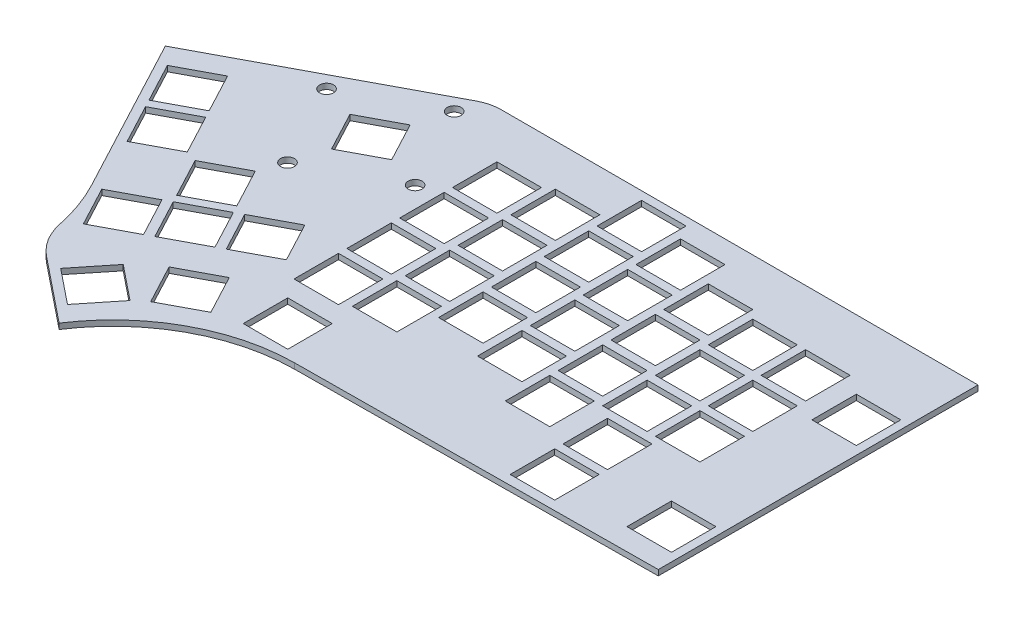
SolidWorks part; units mm, degrees
ref_plane "Front Plane" through (0, 0, 0) normal (0, 0, 1) x (1, 0, 0)
ref_plane "Top Plane" through (0, 0, 0) normal (0, 1, 0) x (1, 0, 0)
ref_plane "Right Plane" through (0, 0, 0) normal (1, 0, 0) x (0, 0, -1)
sketch "Main" plane through (0, 0, 0) normal (0, 1, 0) x (1, 0, 0)
  line L0 (6.4754, 3.5) -> (12.8, 6.5) construction
  line L1 (0, 0) -> (18, 0) construction
  line L2 (0, 0) -> (0, 18) construction
  line L3 (0, 18) -> (18, 18) construction
  line L4 (18, 0) -> (18, 18) construction
  line L5 (2, 16) -> (16, 16)
  line L6 (2, 16) -> (2, 2)
  line L7 (2, 2) -> (16, 2)
  line L8 (16, 16) -> (16, 2)
  line L18 (9, 9) -> (6.4754, 3.5) construction
  line L20 (9, 9) -> (12.8, 6.5) construction
  line L22 (25.4754, 5.5) -> (31.8, 8.5) construction
  line L23 (19, 2) -> (37, 2) construction
  line L24 (19, 2) -> (19, 20) construction
  line L25 (19, 20) -> (37, 20) construction
  line L26 (37, 2) -> (37, 20) construction
  line L27 (21, 18) -> (35, 18)
  line L28 (21, 18) -> (21, 4)
  line L29 (21, 4) -> (35, 4)
  line L30 (35, 18) -> (35, 4)
  line L31 (28, 11) -> (25.4754, 5.5) construction
  line L32 (28, 11) -> (31.8, 8.5) construction
  line L33 (44.4754, 17.5) -> (50.8, 20.5) construction
  line L34 (38, 14) -> (56, 14) construction
  line L35 (38, 14) -> (38, 32) construction
  line L36 (38, 32) -> (56, 32) construction
  line L37 (56, 14) -> (56, 32) construction
  line L38 (40, 30) -> (54, 30)
  line L39 (40, 30) -> (40, 16)
  line L40 (40, 16) -> (54, 16)
  line L41 (54, 30) -> (54, 16)
  line L42 (47, 23) -> (44.4754, 17.5) construction
  line L43 (47, 23) -> (50.8, 20.5) construction
  line L44 (63.4754, 12.5) -> (69.8, 15.5) construction
  line L45 (57, 9) -> (75, 9) construction
  line L46 (57, 9) -> (57, 27) construction
  line L47 (57, 27) -> (75, 27) construction
  line L48 (75, 9) -> (75, 27) construction
  line L49 (59, 25) -> (73, 25)
  line L50 (59, 25) -> (59, 11)
  line L51 (59, 11) -> (73, 11)
  line L52 (73, 25) -> (73, 11)
  line L53 (66, 18) -> (63.4754, 12.5) construction
  line L54 (66, 18) -> (69.8, 15.5) construction
  line L55 (82.4754, 3.5) -> (88.8, 6.5) construction
  line L56 (76, 0) -> (94, 0) construction
  line L57 (76, 0) -> (76, 18) construction
  line L58 (76, 18) -> (94, 18) construction
  line L59 (94, 0) -> (94, 18) construction
  line L60 (78, 16) -> (92, 16)
  line L61 (78, 16) -> (78, 2)
  line L62 (78, 2) -> (92, 2)
  line L63 (92, 16) -> (92, 2)
  line L64 (85, 9) -> (82.4754, 3.5) construction
  line L65 (85, 9) -> (88.8, 6.5) construction
  line L66 (101.4754, 0.5) -> (107.8, 3.5) construction
  line L67 (95, -3) -> (113, -3) construction
  line L68 (95, -3) -> (95, 15) construction
  line L69 (95, 15) -> (113, 15) construction
  line L70 (113, -3) -> (113, 15) construction
  line L71 (97, 13) -> (111, 13)
  line L72 (97, 13) -> (97, -1)
  line L73 (97, -1) -> (111, -1)
  line L74 (111, 13) -> (111, -1)
  line L75 (104, 6) -> (101.4754, 0.5) construction
  line L76 (104, 6) -> (107.8, 3.5) construction
  line L77 (120.4754, 0.5) -> (126.8, 3.5) construction
  line L78 (114, -3) -> (132, -3) construction
  line L79 (114, -3) -> (114, 15) construction
  line L80 (114, 15) -> (132, 15) construction
  line L81 (132, -3) -> (132, 15) construction
  line L82 (116, 13) -> (130, 13)
  line L83 (116, 13) -> (116, -1)
  line L84 (116, -1) -> (130, -1)
  line L85 (130, 13) -> (130, -1)
  line L86 (123, 6) -> (120.4754, 0.5) construction
  line L87 (123, 6) -> (126.8, 3.5) construction
  line L88 (2, -3) -> (16, -3)
  line L89 (2, -3) -> (2, -17)
  line L90 (2, -17) -> (16, -17)
  line L91 (16, -3) -> (16, -17)
  line L92 (21, -1) -> (35, -1)
  line L93 (21, -1) -> (21, -15)
  line L94 (21, -15) -> (35, -15)
  line L95 (35, -1) -> (35, -15)
  line L96 (40, 11) -> (54, 11)
  line L97 (40, 11) -> (40, -3)
  line L98 (40, -3) -> (54, -3)
  line L99 (54, 11) -> (54, -3)
  line L100 (59, 6) -> (73, 6)
  line L101 (59, 6) -> (59, -8)
  line L102 (59, -8) -> (73, -8)
  line L103 (73, 6) -> (73, -8)
  line L104 (78, -3) -> (92, -3)
  line L105 (78, -3) -> (78, -17)
  line L106 (78, -17) -> (92, -17)
  line L107 (92, -3) -> (92, -17)
  line L108 (97, -6) -> (111, -6)
  line L109 (97, -6) -> (97, -20)
  line L110 (97, -20) -> (111, -20)
  line L111 (111, -6) -> (111, -20)
  line L112 (116, -6) -> (130, -6)
  line L113 (116, -6) -> (116, -20)
  line L114 (116, -20) -> (130, -20)
  line L115 (130, -6) -> (130, -20)
  line L116 (6.4754, -15.5) -> (12.8, -12.5) construction
  line L117 (0, -19) -> (18, -19) construction
  line L118 (0, -19) -> (0, -1) construction
  line L119 (0, -1) -> (18, -1) construction
  line L120 (18, -19) -> (18, -1) construction
  line L121 (9, -10) -> (6.4754, -15.5) construction
  line L122 (9, -10) -> (12.8, -12.5) construction
  line L123 (25.4754, -13.5) -> (31.8, -10.5) construction
  line L124 (19, -17) -> (37, -17) construction
  line L125 (19, -17) -> (19, 1) construction
  line L126 (19, 1) -> (37, 1) construction
  line L127 (37, -17) -> (37, 1) construction
  line L128 (28, -8) -> (25.4754, -13.5) construction
  line L129 (28, -8) -> (31.8, -10.5) construction
  line L130 (44.4754, -1.5) -> (50.8, 1.5) construction
  line L131 (38, -5) -> (56, -5) construction
  line L132 (38, -5) -> (38, 13) construction
  line L133 (38, 13) -> (56, 13) construction
  line L134 (56, -5) -> (56, 13) construction
  line L135 (47, 4) -> (44.4754, -1.5) construction
  line L136 (47, 4) -> (50.8, 1.5) construction
  line L137 (63.4754, -6.5) -> (69.8, -3.5) construction
  line L138 (57, -10) -> (75, -10) construction
  line L139 (57, -10) -> (57, 8) construction
  line L140 (57, 8) -> (75, 8) construction
  line L141 (75, -10) -> (75, 8) construction
  line L142 (66, -1) -> (63.4754, -6.5) construction
  line L143 (66, -1) -> (69.8, -3.5) construction
  line L144 (82.4754, -15.5) -> (88.8, -12.5) construction
  line L145 (76, -19) -> (94, -19) construction
  line L146 (76, -19) -> (76, -1) construction
  line L147 (76, -1) -> (94, -1) construction
  line L148 (94, -19) -> (94, -1) construction
  line L149 (85, -10) -> (82.4754, -15.5) construction
  line L150 (85, -10) -> (88.8, -12.5) construction
  line L151 (101.4754, -18.5) -> (107.8, -15.5) construction
  line L152 (95, -22) -> (113, -22) construction
  line L153 (95, -22) -> (95, -4) construction
  line L154 (95, -4) -> (113, -4) construction
  line L155 (113, -22) -> (113, -4) construction
  line L156 (104, -13) -> (101.4754, -18.5) construction
  line L157 (104, -13) -> (107.8, -15.5) construction
  line L158 (120.4754, -18.5) -> (126.8, -15.5) construction
  line L159 (114, -22) -> (132, -22) construction
  line L160 (114, -22) -> (114, -4) construction
  line L161 (114, -4) -> (132, -4) construction
  line L162 (132, -22) -> (132, -4) construction
  line L163 (123, -13) -> (120.4754, -18.5) construction
  line L164 (123, -13) -> (126.8, -15.5) construction
  line L165 (2, -22) -> (16, -22)
  line L166 (2, -22) -> (2, -36)
  line L167 (2, -36) -> (16, -36)
  line L168 (16, -22) -> (16, -36)
  line L169 (21, -20) -> (35, -20)
  line L170 (21, -20) -> (21, -34)
  line L171 (21, -34) -> (35, -34)
  line L172 (35, -20) -> (35, -34)
  line L173 (40, -8) -> (54, -8)
  line L174 (40, -8) -> (40, -22)
  line L175 (40, -22) -> (54, -22)
  line L176 (54, -8) -> (54, -22)
  line L177 (59, -13) -> (73, -13)
  line L178 (59, -13) -> (59, -27)
  line L179 (59, -27) -> (73, -27)
  line L180 (73, -13) -> (73, -27)
  line L181 (78, -22) -> (92, -22)
  line L182 (78, -22) -> (78, -36)
  line L183 (78, -36) -> (92, -36)
  line L184 (92, -22) -> (92, -36)
  line L185 (97, -25) -> (111, -25)
  line L186 (97, -25) -> (97, -39)
  line L187 (97, -39) -> (111, -39)
  line L188 (111, -25) -> (111, -39)
  line L189 (116, -25) -> (130, -25)
  line L190 (116, -25) -> (116, -39)
  line L191 (116, -39) -> (130, -39)
  line L192 (130, -25) -> (130, -39)
  line L193 (6.4754, -34.5) -> (12.8, -31.5) construction
  line L194 (0, -38) -> (18, -38) construction
  line L195 (0, -38) -> (0, -20) construction
  line L196 (0, -20) -> (18, -20) construction
  line L197 (18, -38) -> (18, -20) construction
  line L198 (9, -29) -> (6.4754, -34.5) construction
  line L199 (9, -29) -> (12.8, -31.5) construction
  line L200 (25.4754, -32.5) -> (31.8, -29.5) construction
  line L201 (19, -36) -> (37, -36) construction
  line L202 (19, -36) -> (19, -18) construction
  line L203 (19, -18) -> (37, -18) construction
  line L204 (37, -36) -> (37, -18) construction
  line L205 (28, -27) -> (25.4754, -32.5) construction
  line L206 (28, -27) -> (31.8, -29.5) construction
  line L207 (44.4754, -20.5) -> (50.8, -17.5) construction
  line L208 (38, -24) -> (56, -24) construction
  line L209 (38, -24) -> (38, -6) construction
  line L210 (38, -6) -> (56, -6) construction
  line L211 (56, -24) -> (56, -6) construction
  line L212 (47, -15) -> (44.4754, -20.5) construction
  line L213 (47, -15) -> (50.8, -17.5) construction
  line L214 (63.4754, -25.5) -> (69.8, -22.5) construction
  line L215 (57, -29) -> (75, -29) construction
  line L216 (57, -29) -> (57, -11) construction
  line L217 (57, -11) -> (75, -11) construction
  line L218 (75, -29) -> (75, -11) construction
  line L219 (66, -20) -> (63.4754, -25.5) construction
  line L220 (66, -20) -> (69.8, -22.5) construction
  line L221 (82.4754, -34.5) -> (88.8, -31.5) construction
  line L222 (76, -38) -> (94, -38) construction
  line L223 (76, -38) -> (76, -20) construction
  line L224 (76, -20) -> (94, -20) construction
  line L225 (94, -38) -> (94, -20) construction
  line L226 (85, -29) -> (82.4754, -34.5) construction
  line L227 (85, -29) -> (88.8, -31.5) construction
  line L228 (101.4754, -37.5) -> (107.8, -34.5) construction
  line L229 (95, -41) -> (113, -41) construction
  line L230 (95, -41) -> (95, -23) construction
  line L231 (95, -23) -> (113, -23) construction
  line L232 (113, -41) -> (113, -23) construction
  line L233 (104, -32) -> (101.4754, -37.5) construction
  line L234 (104, -32) -> (107.8, -34.5) construction
  line L235 (120.4754, -37.5) -> (126.8, -34.5) construction
  line L236 (114, -41) -> (132, -41) construction
  line L237 (114, -41) -> (114, -23) construction
  line L238 (114, -23) -> (132, -23) construction
  line L239 (132, -41) -> (132, -23) construction
  line L240 (123, -32) -> (120.4754, -37.5) construction
  line L241 (123, -32) -> (126.8, -34.5) construction
  line L242 (2, -41) -> (16, -41)
  line L243 (2, -41) -> (2, -55)
  line L244 (2, -55) -> (16, -55)
  line L245 (16, -41) -> (16, -55)
  line L246 (21, -39) -> (35, -39)
  line L247 (21, -39) -> (21, -53)
  line L248 (21, -53) -> (35, -53)
  line L249 (35, -39) -> (35, -53)
  line L250 (40, -27) -> (54, -27)
  line L251 (40, -27) -> (40, -41)
  line L252 (40, -41) -> (54, -41)
  line L253 (54, -27) -> (54, -41)
  line L254 (59, -32) -> (73, -32)
  line L255 (59, -32) -> (59, -46)
  line L256 (59, -46) -> (73, -46)
  line L257 (73, -32) -> (73, -46)
  line L258 (78, -41) -> (92, -41)
  line L259 (78, -41) -> (78, -55)
  line L260 (78, -55) -> (92, -55)
  line L261 (92, -41) -> (92, -55)
  line L270 (6.4754, -53.5) -> (12.8, -50.5) construction
  line L271 (0, -57) -> (18, -57) construction
  line L272 (0, -57) -> (0, -39) construction
  line L273 (0, -39) -> (18, -39) construction
  line L274 (18, -57) -> (18, -39) construction
  line L275 (9, -48) -> (6.4754, -53.5) construction
  line L276 (9, -48) -> (12.8, -50.5) construction
  line L277 (25.4754, -51.5) -> (31.8, -48.5) construction
  line L278 (19, -55) -> (37, -55) construction
  line L279 (19, -55) -> (19, -37) construction
  line L280 (19, -37) -> (37, -37) construction
  line L281 (37, -55) -> (37, -37) construction
  line L282 (28, -46) -> (25.4754, -51.5) construction
  line L283 (28, -46) -> (31.8, -48.5) construction
  line L284 (44.4754, -39.5) -> (50.8, -36.5) construction
  line L285 (38, -43) -> (56, -43) construction
  line L286 (38, -43) -> (38, -25) construction
  line L287 (38, -25) -> (56, -25) construction
  line L288 (56, -43) -> (56, -25) construction
  line L289 (47, -34) -> (44.4754, -39.5) construction
  line L290 (47, -34) -> (50.8, -36.5) construction
  line L291 (63.4754, -44.5) -> (69.8, -41.5) construction
  line L292 (57, -48) -> (75, -48) construction
  line L293 (57, -48) -> (57, -30) construction
  line L294 (57, -30) -> (75, -30) construction
  line L295 (75, -48) -> (75, -30) construction
  line L296 (66, -39) -> (63.4754, -44.5) construction
  line L297 (66, -39) -> (69.8, -41.5) construction
  line L298 (82.4754, -53.5) -> (88.8, -50.5) construction
  line L299 (76, -57) -> (94, -57) construction
  line L300 (76, -57) -> (76, -39) construction
  line L301 (76, -39) -> (94, -39) construction
  line L302 (94, -57) -> (94, -39) construction
  line L303 (85, -48) -> (82.4754, -53.5) construction
  line L304 (85, -48) -> (88.8, -50.5) construction
  line L319 (97, -44) -> (111, -44)
  line L320 (97, -44) -> (97, -58)
  line L321 (97, -58) -> (111, -58)
  line L322 (111, -44) -> (111, -58)
  line L323 (116, -44) -> (130, -44)
  line L324 (116, -44) -> (116, -58)
  line L325 (116, -58) -> (130, -58)
  line L326 (130, -44) -> (130, -58)
  line L327 (101.4754, -56.5) -> (107.8, -53.5) construction
  line L328 (95, -60) -> (113, -60) construction
  line L329 (95, -60) -> (95, -42) construction
  line L330 (95, -42) -> (113, -42) construction
  line L331 (113, -60) -> (113, -42) construction
  line L332 (104, -51) -> (101.4754, -56.5) construction
  line L333 (104, -51) -> (107.8, -53.5) construction
  line L334 (120.4754, -56.5) -> (126.8, -53.5) construction
  line L335 (114, -60) -> (132, -60) construction
  line L336 (114, -60) -> (114, -42) construction
  line L337 (114, -42) -> (132, -42) construction
  line L338 (132, -60) -> (132, -42) construction
  line L339 (123, -51) -> (120.4754, -56.5) construction
  line L340 (123, -51) -> (126.8, -53.5) construction
  circle A0 centre (9, 9) radius 2 construction
  circle A1 centre (6.4754, 3.5) radius 1.5 construction
  circle A2 centre (12.8, 6.5) radius 1.5 construction
  circle A6 centre (28, 11) radius 2 construction
  circle A7 centre (25.4754, 5.5) radius 1.5 construction
  circle A8 centre (31.8, 8.5) radius 1.5 construction
  circle A9 centre (47, 23) radius 2 construction
  circle A10 centre (44.4754, 17.5) radius 1.5 construction
  circle A11 centre (50.8, 20.5) radius 1.5 construction
  circle A12 centre (66, 18) radius 2 construction
  circle A13 centre (63.4754, 12.5) radius 1.5 construction
  circle A14 centre (69.8, 15.5) radius 1.5 construction
  circle A15 centre (85, 9) radius 2 construction
  circle A16 centre (82.4754, 3.5) radius 1.5 construction
  circle A17 centre (88.8, 6.5) radius 1.5 construction
  circle A18 centre (104, 6) radius 2 construction
  circle A19 centre (101.4754, 0.5) radius 1.5 construction
  circle A20 centre (107.8, 3.5) radius 1.5 construction
  circle A21 centre (123, 6) radius 2 construction
  circle A22 centre (120.4754, 0.5) radius 1.5 construction
  circle A23 centre (126.8, 3.5) radius 1.5 construction
  circle A24 centre (9, -10) radius 2 construction
  circle A25 centre (6.4754, -15.5) radius 1.5 construction
  circle A26 centre (12.8, -12.5) radius 1.5 construction
  circle A27 centre (28, -8) radius 2 construction
  circle A28 centre (25.4754, -13.5) radius 1.5 construction
  circle A29 centre (31.8, -10.5) radius 1.5 construction
  circle A30 centre (47, 4) radius 2 construction
  circle A31 centre (44.4754, -1.5) radius 1.5 construction
  circle A32 centre (50.8, 1.5) radius 1.5 construction
  circle A33 centre (66, -1) radius 2 construction
  circle A34 centre (63.4754, -6.5) radius 1.5 construction
  circle A35 centre (69.8, -3.5) radius 1.5 construction
  circle A36 centre (85, -10) radius 2 construction
  circle A37 centre (82.4754, -15.5) radius 1.5 construction
  circle A38 centre (88.8, -12.5) radius 1.5 construction
  circle A39 centre (104, -13) radius 2 construction
  circle A40 centre (101.4754, -18.5) radius 1.5 construction
  circle A41 centre (107.8, -15.5) radius 1.5 construction
  circle A42 centre (123, -13) radius 2 construction
  circle A43 centre (120.4754, -18.5) radius 1.5 construction
  circle A44 centre (126.8, -15.5) radius 1.5 construction
  circle A45 centre (9, -29) radius 2 construction
  circle A46 centre (6.4754, -34.5) radius 1.5 construction
  circle A47 centre (12.8, -31.5) radius 1.5 construction
  circle A48 centre (28, -27) radius 2 construction
  circle A49 centre (25.4754, -32.5) radius 1.5 construction
  circle A50 centre (31.8, -29.5) radius 1.5 construction
  circle A51 centre (47, -15) radius 2 construction
  circle A52 centre (44.4754, -20.5) radius 1.5 construction
  circle A53 centre (50.8, -17.5) radius 1.5 construction
  circle A54 centre (66, -20) radius 2 construction
  circle A55 centre (63.4754, -25.5) radius 1.5 construction
  circle A56 centre (69.8, -22.5) radius 1.5 construction
  circle A57 centre (85, -29) radius 2 construction
  circle A58 centre (82.4754, -34.5) radius 1.5 construction
  circle A59 centre (88.8, -31.5) radius 1.5 construction
  circle A60 centre (104, -32) radius 2 construction
  circle A61 centre (101.4754, -37.5) radius 1.5 construction
  circle A62 centre (107.8, -34.5) radius 1.5 construction
  circle A63 centre (123, -32) radius 2 construction
  circle A64 centre (120.4754, -37.5) radius 1.5 construction
  circle A65 centre (126.8, -34.5) radius 1.5 construction
  circle A66 centre (9, -48) radius 2 construction
  circle A67 centre (6.4754, -53.5) radius 1.5 construction
  circle A68 centre (12.8, -50.5) radius 1.5 construction
  circle A69 centre (28, -46) radius 2 construction
  circle A70 centre (25.4754, -51.5) radius 1.5 construction
  circle A71 centre (31.8, -48.5) radius 1.5 construction
  circle A72 centre (47, -34) radius 2 construction
  circle A73 centre (44.4754, -39.5) radius 1.5 construction
  circle A74 centre (50.8, -36.5) radius 1.5 construction
  circle A75 centre (66, -39) radius 2 construction
  circle A76 centre (63.4754, -44.5) radius 1.5 construction
  circle A77 centre (69.8, -41.5) radius 1.5 construction
  circle A78 centre (85, -48) radius 2 construction
  circle A79 centre (82.4754, -53.5) radius 1.5 construction
  circle A80 centre (88.8, -50.5) radius 1.5 construction
  circle A87 centre (104, -51) radius 2 construction
  circle A88 centre (101.4754, -56.5) radius 1.5 construction
  circle A89 centre (107.8, -53.5) radius 1.5 construction
  circle A90 centre (123, -51) radius 2 construction
  circle A91 centre (120.4754, -56.5) radius 1.5 construction
  circle A92 centre (126.8, -53.5) radius 1.5 construction
  point P9 (9, 16)
  point P10 (9, 18)
  point P11 (2, 9)
  point P12 (0, 9)
  point P30 (28, 18)
  point P31 (28, 20)
  point P32 (21, 11)
  point P33 (19, 11)
  point P46 (47, 30)
  point P47 (47, 32)
  point P48 (40, 23)
  point P49 (38, 23)
  point P64 (66, 25)
  point P65 (66, 27)
  point P66 (59, 18)
  point P67 (57, 18)
  point P82 (85, 16)
  point P83 (85, 18)
  point P84 (78, 9)
  point P85 (76, 9)
  point P100 (104, 13)
  point P101 (104, 15)
  point P102 (97, 6)
  point P103 (95, 6)
  point P118 (123, 13)
  point P119 (123, 15)
  point P120 (116, 6)
  point P121 (114, 6)
  dimension "D6" = 4
  dimension "D7" = 3
  dimension "D10" = 1
  dimension "D11" = 5
  dimension "D1" = 18
  dimension "D2" = 14
  dimension "D3" = 3.2
  dimension "D4" = 4.5
  dimension "D5" = 7
  dimension "D8" = 1
  dimension "D9" = 12
  dimension "D12" = 1
  dimension "D13" = 2
  dimension "D14" = 1
  dimension "D15" = 9
  dimension "D16" = 1
  dimension "D17" = 3
  dimension "D18" = 1
  dimension "D20" = 1
  dimension "D19" = 4
sketch "EntBckSp" plane through (0, 0, 0) normal (0, 1, 0) x (1, 0, 0)
  line L0 (0, 0) -> (18, 0) construction
  line L1 (139, 8.25) -> (153, 8.25)
  line L2 (139, 8.25) -> (139, -5.75)
  line L3 (139, -5.75) -> (153, -5.75)
  line L4 (153, 8.25) -> (153, -5.75)
  line L5 (137, 15) -> (155, 15) construction
  line L6 (137, 15) -> (137, -12.5) construction
  line L7 (137, -12.5) -> (155, -12.5) construction
  line L8 (155, 15) -> (155, -12.5) construction
  line L9 (2, 2) -> (16, 2) construction
  line L10 (143.4754, -4.25) -> (146, 1.25) construction
  line L11 (146, 1.25) -> (149.8, -1.25) construction
  line L12 (149.8, -1.25) -> (143.4754, -4.25) construction
  line L13 (6.4754, 3.5) -> (12.8, 6.5) construction
  line L14 (9, 9) -> (6.4754, 3.5) construction
  line L15 (9, 9) -> (12.8, 6.5) construction
  line L16 (114, 15) -> (132, 15) construction
  line L17 (132, -3) -> (132, 15) construction
  line L18 (101.75, -44) -> (115.75, -44)
  line L19 (101.75, -44) -> (101.75, -58)
  line L20 (101.75, -58) -> (115.75, -58)
  line L21 (115.75, -44) -> (115.75, -58)
  line L22 (95, -42) -> (122.5, -42) construction
  line L23 (95, -42) -> (95, -60) construction
  line L24 (95, -60) -> (122.5, -60) construction
  line L25 (122.5, -42) -> (122.5, -60) construction
  line L26 (106.2254, -56.5) -> (108.75, -51) construction
  line L27 (108.75, -51) -> (112.55, -53.5) construction
  line L28 (112.55, -53.5) -> (106.2254, -56.5) construction
  line L29 (95, -41) -> (95, -23) construction
  line L30 (95, -41) -> (113, -41) construction
  line L31 (101.75, -63) -> (115.75, -63)
  line L32 (101.75, -63) -> (101.75, -77)
  line L33 (101.75, -77) -> (115.75, -77)
  line L34 (115.75, -63) -> (115.75, -77)
  line L35 (95, -61) -> (122.5, -61) construction
  line L36 (95, -61) -> (95, -79) construction
  line L37 (95, -79) -> (122.5, -79) construction
  line L38 (122.5, -61) -> (122.5, -79) construction
  line L39 (106.2254, -75.5) -> (108.75, -70) construction
  line L40 (108.75, -70) -> (112.55, -72.5) construction
  line L41 (112.55, -72.5) -> (106.2254, -75.5) construction
  line L42 (139, -58.25) -> (153, -58.25)
  line L43 (139, -58.25) -> (139, -72.25)
  line L44 (139, -72.25) -> (153, -72.25)
  line L45 (153, -58.25) -> (153, -72.25)
  line L46 (137, -51.5) -> (155, -51.5) construction
  line L47 (137, -51.5) -> (137, -79) construction
  line L48 (137, -79) -> (155, -79) construction
  line L49 (155, -51.5) -> (155, -79) construction
  line L50 (143.4754, -70.75) -> (146, -65.25) construction
  line L51 (146, -65.25) -> (149.8, -67.75) construction
  line L52 (149.8, -67.75) -> (143.4754, -70.75) construction
  line L66 (6.75, -64) -> (20.75, -64)
  line L67 (6.75, -64) -> (6.75, -78)
  line L68 (6.75, -78) -> (20.75, -78)
  line L69 (20.75, -64) -> (20.75, -78)
  line L70 (0, -62) -> (27.5, -62) construction
  line L71 (0, -62) -> (0, -80) construction
  line L72 (0, -80) -> (27.5, -80) construction
  line L73 (27.5, -62) -> (27.5, -80) construction
  line L74 (11.2254, -76.5) -> (13.75, -71) construction
  line L75 (13.75, -71) -> (17.55, -73.5) construction
  line L76 (17.55, -73.5) -> (11.2254, -76.5) construction
  line L77 (0, -57) -> (18, -57) construction
  line L78 (0, -57) -> (0, -39) construction
  circle A0 centre (146, 1.25) radius 2 construction
  circle A1 centre (143.4754, -4.25) radius 1.5 construction
  circle A2 centre (149.8, -1.25) radius 1.5 construction
  circle A3 centre (9, 9) radius 2 construction
  circle A4 centre (6.4754, 3.5) radius 1.5 construction
  circle A5 centre (108.75, -51) radius 2 construction
  circle A6 centre (106.2254, -56.5) radius 1.5 construction
  circle A7 centre (112.55, -53.5) radius 1.5 construction
  circle A8 centre (108.75, -70) radius 2 construction
  circle A9 centre (106.2254, -75.5) radius 1.5 construction
  circle A10 centre (112.55, -72.5) radius 1.5 construction
  circle A11 centre (146, -65.25) radius 2 construction
  circle A12 centre (143.4754, -70.75) radius 1.5 construction
  circle A13 centre (149.8, -67.75) radius 1.5 construction
  circle A17 centre (13.75, -71) radius 2 construction
  circle A18 centre (11.2254, -76.5) radius 1.5 construction
  circle A19 centre (17.55, -73.5) radius 1.5 construction
  point P14 (146, 8.25)
  point P15 (146, 15)
  point P16 (139, 1.25)
  point P17 (137, 1.25)
  point P51 (108.75, -44)
  point P52 (108.75, -42)
  point P53 (101.75, -51)
  point P54 (95, -51)
  point P87 (146, -58.25)
  point P88 (146, -51.5)
  point P89 (139, -65.25)
  point P90 (137, -65.25)
  point P105 (13.75, -64)
  point P106 (13.75, -62)
  point P107 (6.75, -71)
  point P108 (0, -71)
  dimension "D1" = 27.5
  dimension "D2" = 5
  dimension "D3" = 1
  dimension "D5" = 1
  dimension "D7" = 5
  dimension "D4" = 2
sketch "MoLngGo" plane through (0, 0, 0) normal (0, 1, 0) x (1, 0, 0)
  line L0 (-23.8647, -75.115) -> (-11.5011, -68.5469)
  line L1 (-23.8647, -75.115) -> (-17.2967, -87.4787)
  line L2 (-11.5011, -68.5469) -> (-4.933, -80.9106)
  line L3 (-17.2967, -87.4787) -> (-4.933, -80.9106)
  line L4 (-28.7977, -70.0922) -> (-12.9016, -61.6476) construction
  line L5 (-28.7977, -70.0922) -> (-15.8962, -94.378) construction
  line L6 (-12.9016, -61.6476) -> (0, -85.9334) construction
  line L7 (-15.8962, -94.378) -> (0, -85.9334) construction
  line L8 (-12.9016, -61.6476) -> (-15.8962, -94.378) construction
  line L9 (-23.8647, -75.115) -> (-4.933, -80.9106) construction
  line L10 (0, -62) -> (0, -80) construction
  line L11 (0, -80) -> (27.5, -80) construction
  line L12 (6.75, -78) -> (20.75, -78) construction
  line L13 (-14.3989, -78.0128) -> (13.75, -131) construction
  line L14 (-14.048, -84.0544) -> (-9.8701, -78.4379) construction
  line L15 (-9.8701, -78.4379) -> (-14.3989, -78.0128) construction
  line L16 (-14.3989, -78.0128) -> (-14.048, -84.0544) construction
  line L17 (17.55, -73.5) -> (11.2254, -76.5) construction
  line L18 (11.2254, -76.5) -> (13.75, -71) construction
  line L19 (13.75, -71) -> (17.55, -73.5) construction
  line L20 (-42.8638, -94.4914) -> (-34.0949, -83.5778)
  line L21 (-42.8638, -94.4914) -> (-31.9502, -103.2603)
  line L22 (-34.0949, -83.5778) -> (-23.1813, -92.3467)
  line L23 (-31.9502, -103.2603) -> (-23.1813, -92.3467)
  line L24 (-49.3784, -91.8226) -> (-38.1041, -77.7908) construction
  line L25 (-49.3784, -91.8226) -> (-27.941, -109.0472) construction
  line L26 (-38.1041, -77.7908) -> (-16.6667, -95.0154) construction
  line L27 (-27.941, -109.0472) -> (-16.6667, -95.0154) construction
  line L28 (-38.1041, -77.7908) -> (-27.941, -109.0472) construction
  line L29 (-42.8638, -94.4914) -> (-23.1813, -92.3467) construction
  line L30 (-33.0225, -93.419) -> (13.75, -131) construction
  line L31 (-30.3163, -98.8319) -> (-28.6936, -92.0226) construction
  line L32 (-28.6936, -92.0226) -> (-33.0225, -93.419) construction
  line L33 (-33.0225, -93.419) -> (-30.3163, -98.8319) construction
  line L34 (-26.6363, -45.1647) -> (-14.2726, -38.5966)
  line L35 (-26.6363, -45.1647) -> (-20.0682, -57.5283)
  line L36 (-14.2726, -38.5966) -> (-7.7045, -50.9603)
  line L37 (-20.0682, -57.5283) -> (-7.7045, -50.9603)
  line L38 (-29.3408, -44.3367) -> (-13.4447, -35.8921) construction
  line L39 (-29.3408, -44.3367) -> (-20.8962, -60.2329) construction
  line L40 (-13.4447, -35.8921) -> (-5, -51.7882) construction
  line L41 (-20.8962, -60.2329) -> (-5, -51.7882) construction
  line L42 (-13.4447, -35.8921) -> (-20.8962, -60.2329) construction
  line L43 (-26.6363, -45.1647) -> (-7.7045, -50.9603) construction
  line L44 (-16.8196, -54.104) -> (-12.6417, -48.4875) construction
  line L45 (-12.6417, -48.4875) -> (-17.1704, -48.0625) construction
  line L46 (-17.1704, -48.0625) -> (-16.8196, -54.104) construction
  line L47 (-43.4156, -54.0785) -> (-31.0519, -47.5104)
  line L48 (-43.4156, -54.0785) -> (-36.8475, -66.4422)
  line L49 (-31.0519, -47.5104) -> (-24.4838, -59.8741)
  line L50 (-36.8475, -66.4422) -> (-24.4838, -59.8741)
  line L51 (-46.1201, -53.2505) -> (-30.2239, -44.8059) construction
  line L52 (-46.1201, -53.2505) -> (-37.6754, -69.1467) construction
  line L53 (-30.2239, -44.8059) -> (-21.7793, -60.702) construction
  line L54 (-37.6754, -69.1467) -> (-21.7793, -60.702) construction
  line L55 (-30.2239, -44.8059) -> (-37.6754, -69.1467) construction
  line L56 (-43.4156, -54.0785) -> (-24.4838, -59.8741) construction
  line L57 (-33.5989, -63.0178) -> (-29.421, -57.4013) construction
  line L58 (-29.421, -57.4013) -> (-33.9497, -56.9763) construction
  line L59 (-33.9497, -56.9763) -> (-33.5989, -63.0178) construction
  line L60 (-60.1948, -62.9923) -> (-47.8312, -56.4242)
  line L61 (-60.1948, -62.9923) -> (-53.6268, -75.356)
  line L62 (-47.8312, -56.4242) -> (-41.2631, -68.7879)
  line L63 (-53.6268, -75.356) -> (-41.2631, -68.7879)
  line L64 (-62.8994, -62.1643) -> (-47.0032, -53.7197) construction
  line L65 (-62.8994, -62.1643) -> (-54.4547, -78.0605) construction
  line L66 (-47.0032, -53.7197) -> (-38.5586, -69.6158) construction
  line L67 (-54.4547, -78.0605) -> (-38.5586, -69.6158) construction
  line L68 (-47.0032, -53.7197) -> (-54.4547, -78.0605) construction
  line L69 (-60.1948, -62.9923) -> (-41.2631, -68.7879) construction
  line L70 (-50.3781, -71.9316) -> (-46.2002, -66.3151) construction
  line L71 (-46.2002, -66.3151) -> (-50.729, -65.8901) construction
  line L72 (-50.729, -65.8901) -> (-50.3781, -71.9316) construction
  line L73 (0, -57) -> (0, -39) construction
  line L74 (-52.3294, -37.2992) -> (-39.9657, -30.7311)
  line L75 (-52.3294, -37.2992) -> (-45.7613, -49.6629)
  line L76 (-39.9657, -30.7311) -> (-33.3976, -43.0948)
  line L77 (-45.7613, -49.6629) -> (-33.3976, -43.0948)
  line L78 (-55.0339, -36.4713) -> (-39.1377, -28.0266) construction
  line L79 (-55.0339, -36.4713) -> (-46.5892, -52.3674) construction
  line L80 (-46.5892, -52.3674) -> (-30.6931, -43.9228) construction
  line L81 (-39.1377, -28.0266) -> (-46.5892, -52.3674) construction
  line L82 (-52.3294, -37.2992) -> (-33.3976, -43.0948) construction
  line L83 (-42.5127, -46.2386) -> (-38.3348, -40.622) construction
  line L84 (-38.3348, -40.622) -> (-42.8635, -40.197) construction
  line L85 (-42.8635, -40.197) -> (-42.5127, -46.2386) construction
  line L86 (-39.1377, -28.0266) -> (-30.6931, -43.9228) construction
  line L96 (0, -19) -> (0, -1) construction
  line L98 (-38.8848, 4.9459) -> (-26.5211, 11.514)
  line L99 (-38.8848, 4.9459) -> (-32.3167, -7.4178)
  line L100 (-78.0224, -29.4337) -> (-65.6588, -22.8657)
  line L101 (-78.0224, -29.4337) -> (-71.4544, -41.7974)
  line L102 (-65.6588, -22.8657) -> (-59.0907, -35.2293)
  line L103 (-71.4544, -41.7974) -> (-59.0907, -35.2293)
  line L104 (-80.727, -28.6058) -> (-64.8308, -20.1611) construction
  line L105 (-80.727, -28.6058) -> (-72.2823, -44.5019) construction
  line L106 (-64.8308, -20.1611) -> (-56.3862, -36.0573) construction
  line L107 (-72.2823, -44.5019) -> (-56.3862, -36.0573) construction
  line L108 (-64.8308, -20.1611) -> (-72.2823, -44.5019) construction
  line L109 (-78.0224, -29.4337) -> (-59.0907, -35.2293) construction
  line L110 (-68.2057, -38.3731) -> (-64.0278, -32.7566) construction
  line L111 (-64.0278, -32.7566) -> (-68.5566, -32.3315) construction
  line L112 (-68.5566, -32.3315) -> (-68.2057, -38.3731) construction
  line L113 (-86.9362, -12.6545) -> (-74.5726, -6.0864)
  line L114 (-86.9362, -12.6545) -> (-80.3682, -25.0181)
  line L115 (-74.5726, -6.0864) -> (-68.0045, -18.4501)
  line L116 (-80.3682, -25.0181) -> (-68.0045, -18.4501)
  line L117 (-89.6408, -11.8265) -> (-73.7446, -3.3819) construction
  line L118 (-89.6408, -11.8265) -> (-81.1961, -27.7227) construction
  line L119 (-73.7446, -3.3819) -> (-65.3, -19.278) construction
  line L120 (-81.1961, -27.7227) -> (-65.3, -19.278) construction
  line L121 (-73.7446, -3.3819) -> (-81.1961, -27.7227) construction
  line L122 (-86.9362, -12.6545) -> (-68.0045, -18.4501) construction
  line L123 (-77.1195, -21.5938) -> (-72.9416, -15.9773) construction
  line L124 (-72.9416, -15.9773) -> (-77.4704, -15.5523) construction
  line L125 (-77.4704, -15.5523) -> (-77.1195, -21.5938) construction
  line L126 (-55.917, -36.9404) -> (-63.3685, -61.2812) construction
  line L127 (-69.1086, -46.213) -> (-50.1769, -52.0086) construction
  line L128 (-59.2919, -55.1524) -> (-55.114, -49.5359) construction
  line L129 (-55.114, -49.5359) -> (-59.6428, -49.1108) construction
  line L130 (-59.6428, -49.1108) -> (-59.2919, -55.1524) construction
  line L131 (-69.1086, -46.213) -> (-56.745, -39.6449) construction
  line L132 (-69.1086, -46.213) -> (-62.5406, -58.5767) construction
  line L133 (-71.8132, -45.3851) -> (-63.3685, -61.2812) construction
  line L134 (-63.3685, -61.2812) -> (-47.4724, -52.8366) construction
  line L135 (-56.745, -39.6449) -> (-50.1769, -52.0086) construction
  line L136 (-62.5406, -58.5767) -> (-50.1769, -52.0086) construction
  line L137 (-55.917, -36.9404) -> (-47.4724, -52.8366) construction
  line L138 (-71.8132, -45.3851) -> (-55.917, -36.9404) construction
  line L139 (-26.5211, 11.514) -> (-19.953, -0.8497)
  line L140 (-32.3167, -7.4178) -> (-19.953, -0.8497)
  line L141 (-41.5893, 5.7739) -> (-25.6932, 14.2185) construction
  line L142 (-41.5893, 5.7739) -> (-33.1447, -10.1223) construction
  line L143 (-25.6932, 14.2185) -> (-17.2485, -1.6776) construction
  line L144 (-33.1447, -10.1223) -> (-17.2485, -1.6776) construction
  line L145 (-25.6932, 14.2185) -> (-33.1447, -10.1223) construction
  line L146 (-38.8848, 4.9459) -> (-19.953, -0.8497) construction
  line L147 (-29.0681, -3.9934) -> (-24.8902, 1.6231) construction
  line L148 (-24.8902, 1.6231) -> (-29.4189, 2.0481) construction
  line L149 (-29.4189, 2.0481) -> (-29.0681, -3.9934) construction
  line L150 (-57.8165, 10.7415) -> (-20.7255, 30.4457) construction
  line L151 (-57.8165, 10.7415) -> (-38.1123, -26.3495) construction
  line L152 (-20.7255, 30.4457) -> (-1.0213, -6.6453) construction
  line L153 (-38.1123, -26.3495) -> (-1.0213, -6.6453) construction
  line L154 (-19.5668, -16.4974) -> (-39.271, 20.5936) construction
  line L155 (-25.6932, 14.2185) -> (-20.7255, 30.4457) construction
  circle A0 centre (13.75, -131) radius 60 construction
  circle A1 centre (-14.3989, -78.0128) radius 2 construction
  circle A2 centre (13.75, -71) radius 2 construction
  circle A3 centre (-14.048, -84.0544) radius 1.5 construction
  circle A4 centre (-9.8701, -78.4379) radius 1.5 construction
  circle A5 centre (11.2254, -76.5) radius 1.5 construction
  circle A6 centre (-33.0225, -93.419) radius 2 construction
  circle A7 centre (-30.3163, -98.8319) radius 1.5 construction
  circle A8 centre (-28.6936, -92.0226) radius 1.5 construction
  circle A9 centre (-17.1704, -48.0625) radius 2 construction
  circle A10 centre (-16.8196, -54.104) radius 1.5 construction
  circle A11 centre (-12.6417, -48.4875) radius 1.5 construction
  circle A12 centre (-33.9497, -56.9763) radius 2 construction
  circle A13 centre (-33.5989, -63.0178) radius 1.5 construction
  circle A14 centre (-29.421, -57.4013) radius 1.5 construction
  circle A15 centre (-50.729, -65.8901) radius 2 construction
  circle A16 centre (-50.3781, -71.9316) radius 1.5 construction
  circle A17 centre (-46.2002, -66.3151) radius 1.5 construction
  circle A18 centre (-42.8635, -40.197) radius 2 construction
  circle A19 centre (-42.5127, -46.2386) radius 1.5 construction
  circle A20 centre (-38.3348, -40.622) radius 1.5 construction
  circle A21 centre (-29.4189, 2.0481) radius 2 construction
  circle A22 centre (-29.0681, -3.9934) radius 1.5 construction
  circle A23 centre (-24.8902, 1.6231) radius 1.5 construction
  circle A24 centre (-68.5566, -32.3315) radius 2 construction
  circle A25 centre (-68.2057, -38.3731) radius 1.5 construction
  circle A26 centre (-64.0278, -32.7566) radius 1.5 construction
  circle A27 centre (-77.4704, -15.5523) radius 2 construction
  circle A28 centre (-77.1195, -21.5938) radius 1.5 construction
  circle A29 centre (-72.9416, -15.9773) radius 1.5 construction
  circle A30 centre (-59.6428, -49.1108) radius 2 construction
  circle A31 centre (-55.114, -49.5359) radius 1.5 construction
  circle A32 centre (-59.2919, -55.1524) radius 1.5 construction
  circle A33 centre (-29.4189, 2.0481) radius 24 construction
  circle A34 centre (-22.3936, 24.9968) radius 1.5
  circle A35 centre (-6.4702, -4.9772) radius 1.5
  circle A36 centre (-36.4443, -20.9006) radius 1.5
  circle A37 centre (-52.3677, 9.0734) radius 1.5
  point P2 (-14.3989, -78.0128)
  point P11 (-14.3989, -78.0128)
  point P39 (-33.0225, -93.419)
  point P46 (-33.0225, -93.419)
  point P56 (-17.1704, -48.0625)
  point P63 (-17.1704, -48.0625)
  point P119 (-29.4189, 2.0481)
  point P126 (-29.4189, 2.0481)
  point P212 (-29.4189, 2.0481)
  dimension "D1" = 120
  dimension "D13" = 48
  dimension "D15" = 3
  dimension "D2" = 1
  dimension "D4" = 1
  dimension "D5" = 5
  dimension "D6" = 5
  dimension "D8" = 1
  dimension "D10" = 1
  dimension "D11" = 1.0213
  dimension "D14" = 42
  dimension "D17" = 1
  dimension "D3" = 3
  dimension "D7" = 2
  dimension "D9" = 4
  dimension "D16" = 4
sketch "Sketch3" plane through (0, 0, 0) normal (0, 1, 0) x (1, 0, 0)
  line L0 (-14.4867, 37) -> (157, 37) construction
  line L1 (160, 34) -> (160, -80.9844) construction
  line L2 (157.0235, -83.9843) -> (27.2686, -85.002) construction
  line L3 (-29.3792, -114.3056) -> (-52.5101, -95.7203) construction
  line L4 (-67.315, -64.5101) -> (-97.3404, -7.9904) construction
  line L5 (-96.0985, -3.9336) -> (-23.0712, 34.8613) construction
  line L6 (38, 32) -> (56, 32) construction
  line L7 (155, 15) -> (155, -12.5) construction
  line L8 (27.5, -80) -> (27.5392, -84.9998) construction
  line L9 (155, -79) -> (155.0392, -83.9998) construction
  line L10 (-49.3784, -91.8226) -> (-27.941, -109.0472) construction
  line L11 (-7.9481, -90.1557) -> (-5.6023, -94.5713) construction
  line L12 (-15.8962, -94.378) -> (0, -85.9334) construction
  line L13 (-14.3989, -78.0128) -> (13.75, -131) construction
  line L14 (-22.3038, -102.0313) -> (-18.4061, -105.1631) construction
  line L15 (-27.941, -109.0472) -> (-16.6667, -95.0154) construction
  line L16 (-33.0225, -93.419) -> (13.75, -131) construction
  line L17 (-89.6408, -11.8265) -> (-81.1961, -27.7227) construction
  line L18 (-89.6408, -11.8265) -> (-73.7446, -3.3819) construction
  line L19 (-49.3784, -91.8226) -> (-38.1041, -77.7908) construction
  line L20 (-54.4547, -78.0605) -> (-38.5586, -69.6158) construction
  line L21 (-62.8994, -62.1643) -> (-47.0032, -53.7197) construction
  line L22 (2, -3) -> (16, -3) construction
  line L23 (2, 16) -> (16, 16) construction
  line L24 (2, 16) -> (2, 2) construction
  line L25 (2, 2) -> (16, 2) construction
  line L26 (16, 16) -> (16, 2) construction
  line L27 (21, 18) -> (35, 18) construction
  line L28 (21, 18) -> (21, 4) construction
  line L29 (21, 4) -> (35, 4) construction
  line L30 (35, 18) -> (35, 4) construction
  line L31 (40, 30) -> (54, 30) construction
  line L32 (40, 30) -> (40, 16) construction
  line L33 (40, 16) -> (54, 16) construction
  line L34 (54, 30) -> (54, 16) construction
  line L35 (59, 25) -> (73, 25) construction
  line L36 (59, 25) -> (59, 11) construction
  line L37 (59, 11) -> (73, 11) construction
  line L38 (73, 25) -> (73, 11) construction
  line L39 (78, 16) -> (92, 16) construction
  line L40 (78, 16) -> (78, 2) construction
  line L41 (78, 2) -> (92, 2) construction
  line L42 (92, 16) -> (92, 2) construction
  line L43 (97, 13) -> (111, 13) construction
  line L44 (97, 13) -> (97, -1) construction
  line L45 (97, -1) -> (111, -1) construction
  line L46 (111, 13) -> (111, -1) construction
  line L47 (116, 13) -> (130, 13) construction
  line L48 (116, 13) -> (116, -1) construction
  line L49 (116, -1) -> (130, -1) construction
  line L50 (130, 13) -> (130, -1) construction
  line L51 (139, 8.25) -> (153, 8.25) construction
  line L52 (139, 8.25) -> (139, -5.75) construction
  line L53 (139, -5.75) -> (153, -5.75) construction
  line L54 (153, 8.25) -> (153, -5.75) construction
  line L55 (139, -58.25) -> (153, -58.25) construction
  line L56 (139, -58.25) -> (139, -72.25) construction
  line L57 (139, -72.25) -> (153, -72.25) construction
  line L58 (153, -58.25) -> (153, -72.25) construction
  line L59 (2, -3) -> (2, -17) construction
  line L60 (2, -17) -> (16, -17) construction
  line L61 (16, -3) -> (16, -17) construction
  line L62 (21, -1) -> (35, -1) construction
  line L63 (21, -1) -> (21, -15) construction
  line L64 (21, -15) -> (35, -15) construction
  line L65 (35, -1) -> (35, -15) construction
  line L66 (40, 11) -> (54, 11) construction
  line L67 (40, 11) -> (40, -3) construction
  line L68 (40, -3) -> (54, -3) construction
  line L69 (54, 11) -> (54, -3) construction
  line L70 (59, 6) -> (73, 6) construction
  line L71 (59, 6) -> (59, -8) construction
  line L72 (59, -8) -> (73, -8) construction
  line L73 (73, 6) -> (73, -8) construction
  line L74 (78, -3) -> (92, -3) construction
  line L75 (78, -3) -> (78, -17) construction
  line L76 (78, -17) -> (92, -17) construction
  line L77 (92, -3) -> (92, -17) construction
  line L78 (97, -6) -> (111, -6) construction
  line L79 (97, -6) -> (97, -20) construction
  line L80 (97, -20) -> (111, -20) construction
  line L81 (111, -6) -> (111, -20) construction
  line L82 (116, -6) -> (130, -6) construction
  line L83 (116, -6) -> (116, -20) construction
  line L84 (116, -20) -> (130, -20) construction
  line L85 (130, -6) -> (130, -20) construction
  line L86 (2, -22) -> (16, -22) construction
  line L87 (2, -22) -> (2, -36) construction
  line L88 (2, -36) -> (16, -36) construction
  line L89 (16, -22) -> (16, -36) construction
  line L90 (21, -20) -> (35, -20) construction
  line L91 (21, -20) -> (21, -34) construction
  line L92 (21, -34) -> (35, -34) construction
  line L93 (35, -20) -> (35, -34) construction
  line L94 (40, -8) -> (54, -8) construction
  line L95 (40, -8) -> (40, -22) construction
  line L96 (40, -22) -> (54, -22) construction
  line L97 (54, -8) -> (54, -22) construction
  line L98 (59, -13) -> (73, -13) construction
  line L99 (59, -13) -> (59, -27) construction
  line L100 (59, -27) -> (73, -27) construction
  line L101 (73, -13) -> (73, -27) construction
  line L102 (78, -22) -> (92, -22) construction
  line L103 (78, -22) -> (78, -36) construction
  line L104 (78, -36) -> (92, -36) construction
  line L105 (92, -22) -> (92, -36) construction
  line L106 (97, -25) -> (111, -25) construction
  line L107 (97, -25) -> (97, -39) construction
  line L108 (97, -39) -> (111, -39) construction
  line L109 (111, -25) -> (111, -39) construction
  line L110 (116, -25) -> (130, -25) construction
  line L111 (116, -25) -> (116, -39) construction
  line L112 (116, -39) -> (130, -39) construction
  line L113 (130, -25) -> (130, -39) construction
  line L114 (2, -41) -> (16, -41) construction
  line L115 (2, -41) -> (2, -55) construction
  line L116 (2, -55) -> (16, -55) construction
  line L117 (16, -41) -> (16, -55) construction
  line L118 (21, -39) -> (35, -39) construction
  line L119 (21, -39) -> (21, -53) construction
  line L120 (21, -53) -> (35, -53) construction
  line L121 (35, -39) -> (35, -53) construction
  line L122 (40, -27) -> (54, -27) construction
  line L123 (40, -27) -> (40, -41) construction
  line L124 (40, -41) -> (54, -41) construction
  line L125 (54, -27) -> (54, -41) construction
  line L126 (59, -32) -> (73, -32) construction
  line L127 (59, -32) -> (59, -46) construction
  line L128 (59, -46) -> (73, -46) construction
  line L129 (73, -32) -> (73, -46) construction
  line L130 (78, -41) -> (92, -41) construction
  line L131 (78, -41) -> (78, -55) construction
  line L132 (78, -55) -> (92, -55) construction
  line L133 (92, -41) -> (92, -55) construction
  line L142 (97, -44) -> (111, -44) [skipped]
  line L143 (97, -44) -> (97, -58) [skipped]
  line L144 (97, -58) -> (111, -58) [skipped]
  line L145 (111, -44) -> (111, -58) [skipped]
  line L146 (116, -44) -> (130, -44) [skipped]
  line L147 (116, -44) -> (116, -58) [skipped]
  line L148 (116, -58) -> (130, -58) [skipped]
  line L149 (130, -44) -> (130, -58) [skipped]
  line L150 (-86.9362, -12.6545) -> (-74.5726, -6.0864) construction
  line L151 (6.75, -64) -> (20.75, -64) construction
  line L152 (6.75, -64) -> (6.75, -78) construction
  line L153 (6.75, -78) -> (20.75, -78) construction
  line L154 (20.75, -64) -> (20.75, -78) construction
  line L155 (101.75, -44) -> (115.75, -44) construction
  line L156 (101.75, -44) -> (101.75, -58) construction
  line L157 (101.75, -58) -> (115.75, -58) construction
  line L158 (115.75, -44) -> (115.75, -58) construction
  line L159 (101.75, -63) -> (115.75, -63) construction
  line L160 (101.75, -63) -> (101.75, -77) construction
  line L161 (101.75, -77) -> (115.75, -77) construction
  line L162 (115.75, -63) -> (115.75, -77) construction
  line L163 (-86.9362, -12.6545) -> (-80.3682, -25.0181) construction
  line L164 (-74.5726, -6.0864) -> (-68.0045, -18.4501) construction
  line L165 (-80.3682, -25.0181) -> (-68.0045, -18.4501) construction
  line L166 (-65.6588, -22.8657) -> (-78.0224, -29.4337) construction
  line L167 (-65.6588, -22.8657) -> (-59.0907, -35.2293) construction
  line L168 (-78.0224, -29.4337) -> (-71.4544, -41.7974) construction
  line L169 (-59.0907, -35.2293) -> (-71.4544, -41.7974) construction
  line L170 (-52.3294, -37.2992) -> (-39.9657, -30.7311) construction
  line L171 (-52.3294, -37.2992) -> (-45.7613, -49.6629) construction
  line L172 (-39.9657, -30.7311) -> (-33.3976, -43.0948) construction
  line L173 (-45.7613, -49.6629) -> (-33.3976, -43.0948) construction
  line L174 (-26.6363, -45.1647) -> (-14.2726, -38.5966) construction
  line L175 (-26.6363, -45.1647) -> (-20.0682, -57.5283) construction
  line L176 (-14.2726, -38.5966) -> (-7.7045, -50.9603) construction
  line L177 (-20.0682, -57.5283) -> (-7.7045, -50.9603) construction
  line L178 (-31.0519, -47.5104) -> (-43.4156, -54.0785) construction
  line L179 (-31.0519, -47.5104) -> (-24.4838, -59.8741) construction
  line L180 (-43.4156, -54.0785) -> (-36.8475, -66.4422) construction
  line L181 (-24.4838, -59.8741) -> (-36.8475, -66.4422) construction
  line L182 (-47.8312, -56.4242) -> (-60.1948, -62.9923) construction
  line L183 (-47.8312, -56.4242) -> (-41.2631, -68.7879) construction
  line L184 (-60.1948, -62.9923) -> (-53.6268, -75.356) construction
  line L185 (-41.2631, -68.7879) -> (-53.6268, -75.356) construction
  line L186 (-36.8475, -66.4422) -> (-24.4838, -59.8741) construction
  line L187 (-34.0949, -83.5778) -> (-42.8638, -94.4914) construction
  line L188 (-34.0949, -83.5778) -> (-23.1813, -92.3467) construction
  line L189 (-42.8638, -94.4914) -> (-31.9502, -103.2603) construction
  line L190 (-23.1813, -92.3467) -> (-31.9502, -103.2603) construction
  line L191 (-23.8647, -75.115) -> (-11.5011, -68.5469) construction
  line L192 (-23.8647, -75.115) -> (-17.2967, -87.4787) construction
  line L193 (-11.5011, -68.5469) -> (-4.933, -80.9106) construction
  line L194 (-17.2967, -87.4787) -> (-4.933, -80.9106) construction
  line L195 (157.0408, -86.1842) -> (27.2859, -87.2019) construction
  line L196 (-20.7255, 30.4457) -> (-1.0213, -6.6453) construction
  line L197 (-38.8848, 4.9459) -> (-26.5211, 11.514) construction
  line L198 (-38.8848, 4.9459) -> (-32.3167, -7.4178) construction
  line L199 (-26.5211, 11.514) -> (-19.953, -0.8497) construction
  line L200 (-32.3167, -7.4178) -> (-19.953, -0.8497) construction
  line L201 (-57.8165, 10.7415) -> (-20.7255, 30.4457) construction
  line L202 (-30.7572, -116.0206) -> (-53.8881, -97.4353) construction
  line L203 (-69.2578, -65.5422) -> (-99.2833, -9.0225) construction
  line L204 (-97.1306, -1.9907) -> (-24.1034, 36.8042) construction
  line L205 (-14.4867, 39.2) -> (157, 39.2) construction
  line L206 (162.2, 34) -> (162.2, -80.9844) construction
  line L207 (1, -2) -> (17, -2)
  line L208 (17, -2) -> (17, -18)
  line L209 (1, -18) -> (17, -18)
  line L210 (1, -2) -> (1, -18)
  line L211 (1, 17) -> (17, 17)
  line L212 (17, 17) -> (17, 1)
  line L213 (1, 1) -> (17, 1)
  line L214 (1, 17) -> (1, 1)
  line L215 (20, 19) -> (36, 19)
  line L216 (36, 19) -> (36, 3)
  line L217 (20, 3) -> (36, 3)
  line L218 (20, 19) -> (20, 3)
  line L219 (39, 31) -> (55, 31)
  line L220 (55, 31) -> (55, 15)
  line L221 (39, 15) -> (55, 15)
  line L222 (39, 31) -> (39, 15)
  line L223 (58, 26) -> (74, 26)
  line L224 (74, 26) -> (74, 10)
  line L225 (58, 10) -> (74, 10)
  line L226 (58, 26) -> (58, 10)
  line L227 (77, 17) -> (93, 17)
  line L228 (93, 17) -> (93, 1)
  line L229 (77, 1) -> (93, 1)
  line L230 (77, 17) -> (77, 1)
  line L231 (96, 14) -> (112, 14)
  line L232 (112, 14) -> (112, -2)
  line L233 (96, -2) -> (112, -2)
  line L234 (96, 14) -> (96, -2)
  line L235 (115, 14) -> (131, 14)
  line L236 (131, 14) -> (131, -2)
  line L237 (115, -2) -> (131, -2)
  line L238 (115, 14) -> (115, -2)
  line L239 (138, 9.25) -> (154, 9.25)
  line L240 (154, 9.25) -> (154, -6.75)
  line L241 (138, -6.75) -> (154, -6.75)
  line L242 (138, 9.25) -> (138, -6.75)
  line L243 (138, -57.25) -> (154, -57.25)
  line L244 (154, -57.25) -> (154, -73.25)
  line L245 (138, -73.25) -> (154, -73.25)
  line L246 (138, -57.25) -> (138, -73.25)
  line L247 (20, 0) -> (36, 0)
  line L248 (36, 0) -> (36, -16)
  line L249 (20, -16) -> (36, -16)
  line L250 (20, 0) -> (20, -16)
  line L251 (39, 12) -> (55, 12)
  line L252 (55, 12) -> (55, -4)
  line L253 (39, -4) -> (55, -4)
  line L254 (39, 12) -> (39, -4)
  line L255 (58, 7) -> (74, 7)
  line L256 (74, 7) -> (74, -9)
  line L257 (58, -9) -> (74, -9)
  line L258 (58, 7) -> (58, -9)
  line L259 (77, -2) -> (93, -2)
  line L260 (93, -2) -> (93, -18)
  line L261 (77, -18) -> (93, -18)
  line L262 (77, -2) -> (77, -18)
  line L263 (96, -5) -> (112, -5)
  line L264 (112, -5) -> (112, -21)
  line L265 (96, -21) -> (112, -21)
  line L266 (96, -5) -> (96, -21)
  line L267 (115, -5) -> (131, -5)
  line L268 (131, -5) -> (131, -21)
  line L269 (115, -21) -> (131, -21)
  line L270 (115, -5) -> (115, -21)
  line L271 (1, -21) -> (17, -21)
  line L272 (17, -21) -> (17, -37)
  line L273 (1, -37) -> (17, -37)
  line L274 (1, -21) -> (1, -37)
  line L275 (20, -19) -> (36, -19)
  line L276 (36, -19) -> (36, -35)
  line L277 (20, -35) -> (36, -35)
  line L278 (20, -19) -> (20, -35)
  line L279 (39, -7) -> (55, -7)
  line L280 (55, -7) -> (55, -23)
  line L281 (39, -23) -> (55, -23)
  line L282 (39, -7) -> (39, -23)
  line L283 (58, -12) -> (74, -12)
  line L284 (74, -12) -> (74, -28)
  line L285 (58, -28) -> (74, -28)
  line L286 (58, -12) -> (58, -28)
  line L287 (77, -21) -> (93, -21)
  line L288 (93, -21) -> (93, -37)
  line L289 (77, -37) -> (93, -37)
  line L290 (77, -21) -> (77, -37)
  line L291 (96, -24) -> (112, -24)
  line L292 (112, -24) -> (112, -40)
  line L293 (96, -40) -> (112, -40)
  line L294 (96, -24) -> (96, -40)
  line L295 (115, -24) -> (131, -24)
  line L296 (131, -24) -> (131, -40)
  line L297 (115, -40) -> (131, -40)
  line L298 (115, -24) -> (115, -40)
  line L299 (1, -40) -> (17, -40)
  line L300 (17, -40) -> (17, -56)
  line L301 (1, -56) -> (17, -56)
  line L302 (1, -40) -> (1, -56)
  line L303 (20, -38) -> (36, -38)
  line L304 (36, -38) -> (36, -54)
  line L305 (20, -54) -> (36, -54)
  line L306 (20, -38) -> (20, -54)
  line L307 (39, -26) -> (55, -26)
  line L308 (55, -26) -> (55, -42)
  line L309 (39, -42) -> (55, -42)
  line L310 (39, -26) -> (39, -42)
  line L311 (58, -31) -> (74, -31)
  line L312 (74, -31) -> (74, -47)
  line L313 (58, -47) -> (74, -47)
  line L314 (58, -31) -> (58, -47)
  line L315 (77, -40) -> (93, -40)
  line L316 (93, -40) -> (93, -56)
  line L317 (77, -56) -> (93, -56)
  line L318 (77, -40) -> (77, -56)
  line L319 (-88.2885, -12.2405) -> (-74.1586, -4.7341)
  line L320 (-74.1586, -4.7341) -> (-66.6522, -18.864)
  line L321 (-80.7821, -26.3704) -> (-66.6522, -18.864)
  line L322 (-88.2885, -12.2405) -> (-80.7821, -26.3704)
  line L323 (5.75, -63) -> (21.75, -63)
  line L324 (21.75, -63) -> (21.75, -79)
  line L325 (5.75, -79) -> (21.75, -79)
  line L326 (5.75, -63) -> (5.75, -79)
  line L327 (100.75, -43) -> (116.75, -43)
  line L328 (116.75, -43) -> (116.75, -59)
  line L329 (100.75, -59) -> (116.75, -59)
  line L330 (100.75, -43) -> (100.75, -59)
  line L331 (100.75, -62) -> (116.75, -62)
  line L332 (116.75, -62) -> (116.75, -78)
  line L333 (100.75, -78) -> (116.75, -78)
  line L334 (100.75, -62) -> (100.75, -78)
  line L335 (-65.2448, -21.5134) -> (-79.3747, -29.0198)
  line L336 (-79.3747, -29.0198) -> (-71.8683, -43.1497)
  line L337 (-57.7384, -35.6433) -> (-71.8683, -43.1497)
  line L338 (-65.2448, -21.5134) -> (-57.7384, -35.6433)
  line L339 (-53.6816, -36.8852) -> (-39.5517, -29.3789)
  line L340 (-39.5517, -29.3789) -> (-32.0453, -43.5088)
  line L341 (-46.1753, -51.0151) -> (-32.0453, -43.5088)
  line L342 (-53.6816, -36.8852) -> (-46.1753, -51.0151)
  line L343 (-27.9885, -44.7507) -> (-13.8586, -37.2443)
  line L344 (-13.8586, -37.2443) -> (-6.3523, -51.3743)
  line L345 (-20.4822, -58.8806) -> (-6.3523, -51.3743)
  line L346 (-27.9885, -44.7507) -> (-20.4822, -58.8806)
  line L347 (-30.6379, -46.1581) -> (-44.7678, -53.6645)
  line L348 (-44.7678, -53.6645) -> (-37.2615, -67.7944)
  line L349 (-23.1315, -60.2881) -> (-37.2615, -67.7944)
  line L350 (-30.6379, -46.1581) -> (-23.1315, -60.2881)
  line L351 (-47.4172, -55.0719) -> (-61.5471, -62.5783)
  line L352 (-61.5471, -62.5783) -> (-54.0407, -76.7082)
  line L353 (-39.9108, -69.2019) -> (-54.0407, -76.7082)
  line L354 (-47.4172, -55.0719) -> (-39.9108, -69.2019)
  line L355 (-34.2481, -82.1719) -> (-44.2697, -94.6446)
  line L356 (-44.2697, -94.6446) -> (-31.797, -104.6662)
  line L357 (-21.7754, -92.1935) -> (-31.797, -104.6662)
  line L358 (-34.2481, -82.1719) -> (-21.7754, -92.1935)
  line L359 (-25.217, -74.701) -> (-11.0871, -67.1947)
  line L360 (-11.0871, -67.1947) -> (-3.5807, -81.3246)
  line L361 (-17.7106, -88.831) -> (-3.5807, -81.3246)
  line L362 (-25.217, -74.701) -> (-17.7106, -88.831)
  line L363 (-40.2371, 5.3599) -> (-26.1071, 12.8662)
  line L364 (-26.1071, 12.8662) -> (-18.6008, -1.2637)
  line L365 (-32.7307, -8.77) -> (-18.6008, -1.2637)
  line L366 (-40.2371, 5.3599) -> (-32.7307, -8.77)
  line L367 (-94.6911, -6.583) -> (-21.6638, 32.212)
  line L368 (-14.4867, 34) -> (157, 34)
  line L369 (157, 34) -> (157, -80.9844)
  line L370 (157, -80.9844) -> (27.2451, -82.0021)
  line L371 (-27.5002, -111.967) -> (-50.6311, -93.3817)
  line L372 (-64.6656, -63.1026) -> (-94.6911, -6.583)
  arc A0 (27.2686, -85.002) -> (-24.9859, -113.6036) centre (27.7622, -147.9386) ccw construction
  arc A1 (-52.5101, -95.7203) -> (-61.1426, -81.6134) centre (-37.1862, -76.6484) cw construction
  arc A2 (-61.1426, -81.6134) -> (-67.315, -64.5101) centre (-124.053, -94.6515) ccw construction
  arc A3 (-23.0712, 34.8613) -> (-14.4867, 37) centre (-14.4867, 18.7019) cw construction
  arc A4 (-97.3404, -7.9904) -> (-96.0985, -3.9336) centre (-94.6911, -6.583) cw construction
  arc A5 (-24.9859, -113.6036) -> (-29.3792, -114.3056) centre (-27.5002, -111.967) cw construction
  arc A6 (160, -80.9844) -> (157.0235, -83.9843) centre (157, -80.9844) cw construction
  arc A7 (157, 37) -> (160, 34) centre (157, 34) cw construction
  circle A8 centre (-22.3936, 24.9968) radius 1.5 construction
  circle A9 centre (-6.4702, -4.9772) radius 1.5 construction
  circle A10 centre (-36.4443, -20.9006) radius 1.5 construction
  circle A11 centre (-52.3677, 9.0734) radius 1.5 construction
  circle A12 centre (-22.3936, 24.9968) radius 1.5 construction
  arc A13 (27.2859, -87.2019) -> (-23.1421, -114.8037) centre (27.7622, -147.9386) ccw construction
  arc A14 (-23.1421, -114.8037) -> (-30.7572, -116.0206) centre (-27.5002, -111.967) cw construction
  arc A15 (-53.8881, -97.4353) -> (-63.2968, -82.0598) centre (-37.1862, -76.6484) cw construction
  arc A16 (-63.2968, -82.0598) -> (-69.2578, -65.5422) centre (-124.053, -94.6515) ccw construction
  arc A17 (-99.2833, -9.0225) -> (-97.1306, -1.9907) centre (-94.6911, -6.583) cw construction
  arc A18 (-24.1034, 36.8042) -> (-14.4867, 39.2) centre (-14.4867, 18.7019) cw construction
  arc A19 (157, 39.2) -> (162.2, 34) centre (157, 34) cw construction
  arc A20 (162.2, -80.9844) -> (157.0408, -86.1842) centre (157, -80.9844) cw construction
  circle A21 centre (-22.3936, 24.9968) radius 2.5
  circle A22 centre (-6.4702, -4.9772) radius 2.5
  circle A23 centre (-36.4443, -20.9006) radius 2.5
  circle A24 centre (-52.3677, 9.0734) radius 2.5
  arc A25 (-21.6638, 32.212) -> (-14.4867, 34) centre (-14.4867, 18.7019) cw
  arc A26 (157, 34) -> (157, 34) centre (157, 34) cw
  arc A27 (157, -80.9844) -> (157, -80.9844) centre (157, -80.9844) cw
  arc A28 (27.2451, -82.0021) -> (-27.5002, -111.967) centre (27.7622, -147.9386) ccw
  arc A29 (-27.5002, -111.967) -> (-27.5002, -111.967) centre (-27.5002, -111.967) cw
  arc A30 (-50.6311, -93.3817) -> (-58.205, -81.0046) centre (-37.1862, -76.6484) cw
  arc A31 (-58.205, -81.0046) -> (-64.6656, -63.1026) centre (-124.053, -94.6515) ccw
  arc A32 (-94.6911, -6.583) -> (-94.6911, -6.583) centre (-94.6911, -6.583) cw
  dimension "D7" = 3
  dimension "D1" = 5
  dimension "D2" = 5
  dimension "D3" = 5
  dimension "D4" = 5
  dimension "D5" = 5
  dimension "D6" = 5
  dimension "D9" = 2.2
  dimension "D10" = 1
  dimension "D11" = 3
  dimension "D8" = 4
extrude "Laser" add sketch "Sketch3" against normal blind 2
